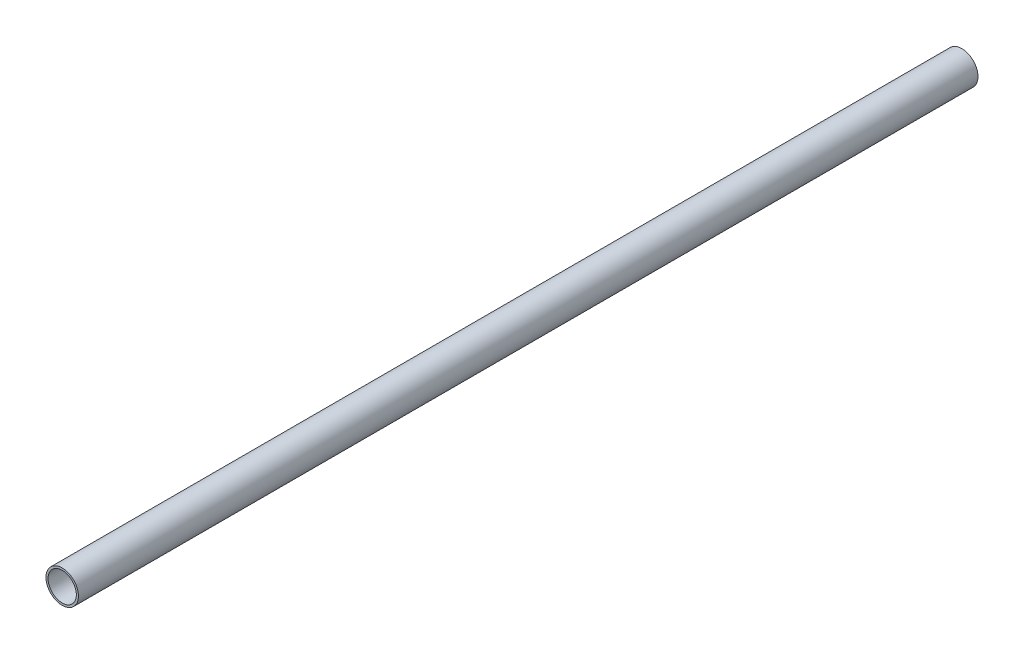
SolidWorks part; units mm, degrees
material "Copper"
ref_plane "Front" through (0, 0, 0) normal (0, 0, 1) x (1, 0, 0)
ref_plane "Top" through (0, 0, 0) normal (0, 1, 0) x (1, 0, 0)
ref_plane "Right" through (0, 0, 0) normal (1, 0, 0) x (0, 0, -1)
sketch "Sketch1" plane through (0, 0, 0) normal (0, 0, 1) x (1, 0, 0)
  circle A0 centre (0, 0) radius 7.9375
  circle A1 centre (0, 0) radius 6.9215
  dimension "D1" = 15.875
  dimension "D2" = 13.843
extrude "Boss-Extrude1" add sketch "Sketch1" along normal mid plane 440
